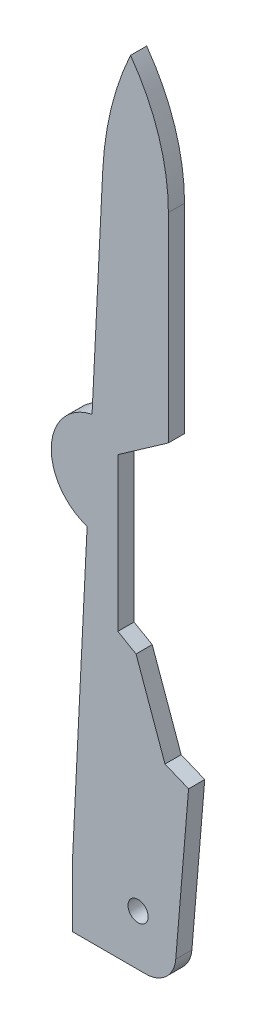
SolidWorks part; units mm, degrees
ref_plane "Płaszczyzna przednia" through (0, 0, 0) normal (0, 0, 1) x (1, 0, 0)
ref_plane "Płaszczyzna górna" through (0, 0, 0) normal (0, 1, 0) x (1, 0, 0)
ref_plane "Płaszczyzna prawa" through (0, 0, 0) normal (1, 0, 0) x (0, 0, -1)
sketch "Sketch1" plane through (0, 0, 0) normal (0, 0, 1) x (1, 0, 0)
  line L0 (0, 67) -> (11.5, 66.2684) construction
  line L5 (-1.2347, 47.3285) -> (11.5, 46.5184) construction
  line L6 (0, 0) -> (0, 6)
  line L7 (0, 6) -> (3.0065, 66.8087)
  line L8 (9.5, 66.3957) -> (9.5, 46.6457)
  line L9 (9.5, 46.6457) -> (4.5, 43.1446)
  line L10 (4.5, 43.1446) -> (4.5, 27.9946)
  line L11 (4.5, 27.9946) -> (6.3, 26.9554)
  line L12 (6.3, 26.9554) -> (9.1658, 18.9519)
  line L13 (9.1658, 18.9519) -> (11.5, 17.9946)
  line L14 (11.5, 17.9946) -> (10, 0)
  line L15 (10, 0) -> (0, 0)
  arc A0 (3.0065, 66.8087) -> (5.75, 78) centre (33.3164, 65.3102) cw
  arc A1 (5.75, 78) -> (9.5, 66.3957) centre (-10.3298, 66.3957) cw
  arc A2 (1.9445, 45.3285) -> (1.4576, 35.4812) centre (3.0065, 40.3403) ccw
  point P1 (1.9445, 45.3285)
  point P2 (0, 0)
  dimension "D9" = 5.1
  dimension "D6" = 6
  dimension "D10" = 2
  dimension "D11" = 125
  dimension "D12" = 5
  dimension "D13" = 15.15
  dimension "D14" = 132
  dimension "D15" = 120
  dimension "D16" = 10
  dimension "D17" = 1.8
  dimension "D18" = 10
extrude "Boss-Extrude3" add sketch "Sketch1" along normal mid plane 1.6 contours A1 A0 L7 L6 L15 L14 L13 L12 L11 L10 L9 L8 | L7 A2
sketch "Sketch2" plane through (0, 0, 0.8) normal (0, 0, 1) x (1, 0, 0)
  line L0 (10, 0) -> (0, 0) construction
  line L1 (0, 0) -> (0, 6) construction
  circle A0 centre (6.5, 5.0135) radius 1
  dimension "D3" = 2
  dimension "D1" = 5.0135
  dimension "D2" = 6.5
fillet "Fillet2" radius 3 1 edges at (10, 0, 0)
extrude "Cut-Extrude1" cut sketch "Sketch2" against normal through all
